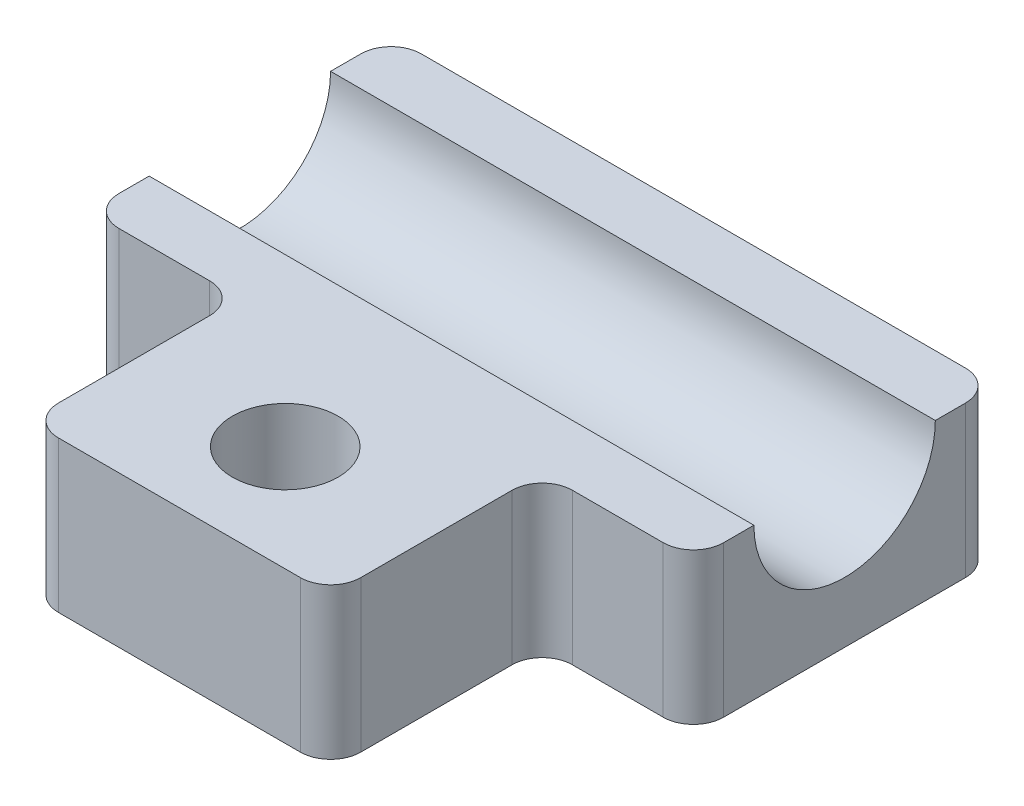
SolidWorks part; units mm, degrees
ref_plane "Front" through (0, 0, 0) normal (0, 0, 1) x (1, 0, 0)
ref_plane "Top" through (0, 0, 0) normal (0, 1, 0) x (1, 0, 0)
ref_plane "Right" through (0, 0, 0) normal (1, 0, 0) x (0, 0, -1)
sketch "Sketch1" plane through (0, 0, 0) normal (0, 1, 0) x (1, 0, 0)
  line L0 (-10, -10) -> (-20, -10)
  line L1 (20, -10) -> (10, -10)
  line L2 (20, -10) -> (20, 10)
  line L3 (20, 10) -> (-20, 10)
  line L4 (-20, -10) -> (-20, 10)
  line L5 (20, -10) -> (-20, 10) construction
  line L6 (20, 10) -> (-20, -10) construction
  line L8 (-10, -10) -> (-10, -24)
  line L9 (-10, -24) -> (10, -24)
  line L10 (10, -10) -> (10, -24)
  line L11 (0, -24) -> (0, -17) construction
  line L12 (-10, -17) -> (10, -17) construction
  point P0 (0, 0)
  point P222 (0, -17)
  dimension "D1" = 20
  dimension "D2" = 40
  dimension "D3" = 20
  dimension "D4" = 14
  dimension "D5" = 10
extrude "Boss-Extrude1" add sketch "Sketch1" along normal blind 10
sketch "Sketch2" plane through (0, 10, 0) normal (0, 1, 0) x (1, 0, 0)
  line L0 (-10, -24) -> (10, -24) construction
  line L1 (-10, -10) -> (-10, -24) construction
  circle A0 centre (0, -17) radius 3.5
  dimension "D1" = 7
  dimension "D2" = 7
  dimension "D3" = 10
extrude "Cut-Extrude1" cut sketch "Sketch2" against normal blind 10
sketch "Sketch3" plane through (20, 0, 0) normal (1, 0, 0) x (0, 0, -1)
  line L0 (-10, 10) -> (10, 10) construction
  circle A0 centre (0, 10) radius 6
extrude "Cut-Extrude2" cut sketch "Sketch3" against normal through all
fillet "Fillet1" radius 2 8 edges at (-10, 5, 24) (-10, 5, 10) (-20, 5, 10) (-20, 5, -10) (20, 5, -10) (20, 5, 10) (10, 5, 10) (10, 5, 24)
